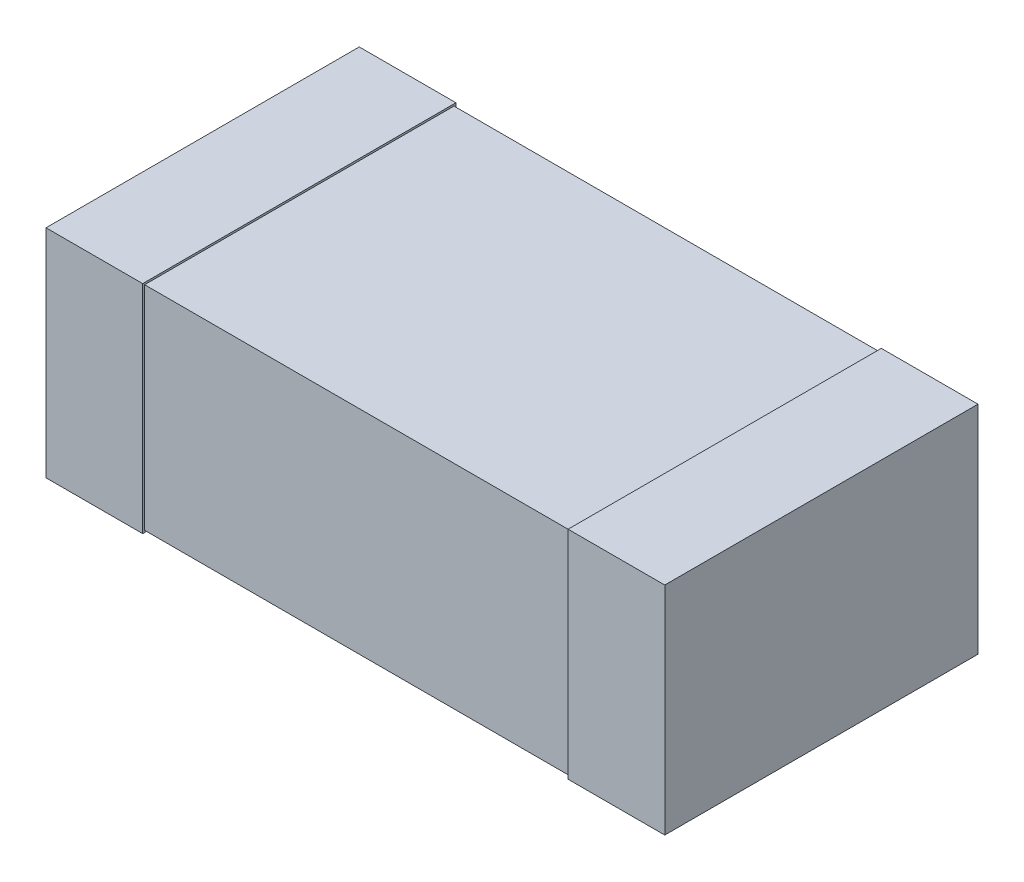
SolidWorks part; units mm, degrees
ref_plane "前视基准面" through (0, 0, 0) normal (0, 0, 1) x (1, 0, 0)
ref_plane "上视基准面" through (0, 0, 0) normal (0, 1, 0) x (1, 0, 0)
ref_plane "右视基准面" through (0, 0, 0) normal (1, 0, 0) x (0, 0, -1)
sketch "草图1" plane through (0, 0, 0) normal (0, 1, 0) x (1, 0, 0)
  line L0 (-3.4256, 0) -> (1.6422, 0) construction
  line L1 (-1.6, 0.8) -> (1.6, 0.8)
  line L2 (-1.6, 0.8) -> (-1.6, -0.8)
  line L3 (-1.6, -0.8) -> (1.6, -0.8)
  line L4 (1.6, 0.8) -> (1.6, -0.8)
  line L5 (0, 2.0678) -> (0, -1.7918) construction
  dimension "D1" = 1.6
  dimension "D2" = 3.2
extrude "凸台-拉伸1" add sketch "草图1" along normal blind 1.1
sketch "草图2" plane through (-1.6, 0, 0) normal (-1, 0, 0) x (0, 0, 1)
  line L8 (-0.81, -0.01) -> (0.81, -0.01)
  line L9 (0.81, -0.01) -> (0.81, 1.11)
  line L10 (0.81, 1.11) -> (-0.81, 1.11)
  line L11 (-0.81, 1.11) -> (-0.81, -0.01)
  line L12 (-0.81, -0.01) -> (0.81, -0.01)
  line L13 (0.81, -0.01) -> (0.81, 1.11)
  line L14 (0.81, 1.11) -> (-0.81, 1.11)
  line L15 (-0.81, 1.11) -> (-0.81, -0.01)
  dimension "D1" = 0.01
extrude "凸台-拉伸2" add sketch "草图2" against normal blind 0.5
mirror "镜向1" about plane through (0, 0, 0) normal (1, 0, 0) of "凸台-拉伸2"
